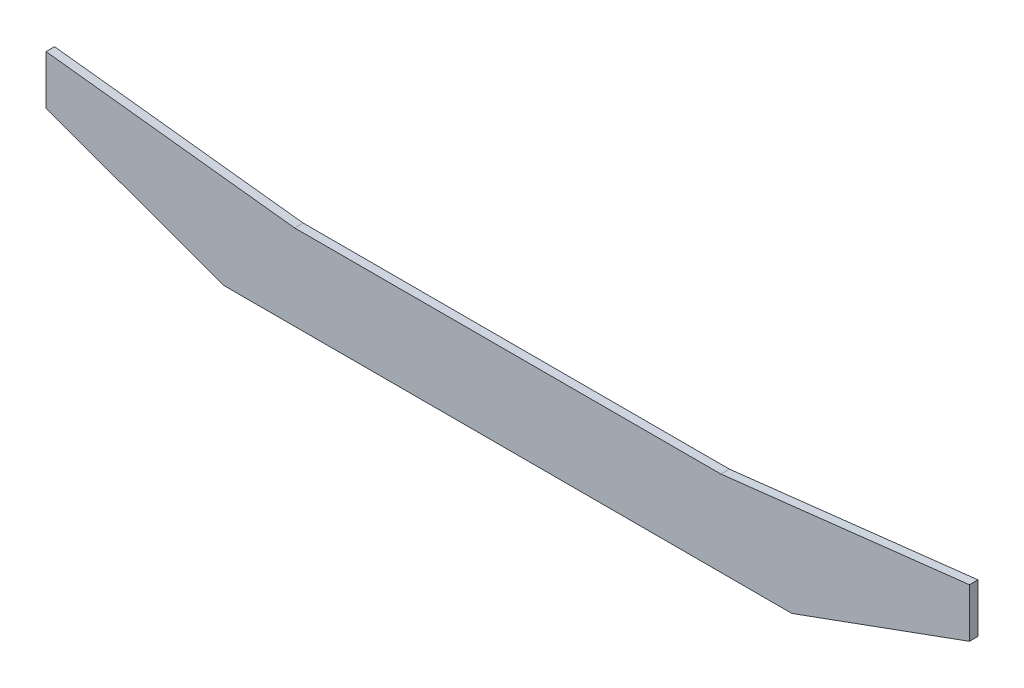
SolidWorks part; units mm, degrees
ref_plane "Спереди" through (0, 0, 0) normal (0, 0, 1) x (1, 0, 0)
ref_plane "Сверху" through (0, 0, 0) normal (0, 1, 0) x (1, 0, 0)
ref_plane "Справа" through (0, 0, 0) normal (1, 0, 0) x (0, 0, -1)
sketch "Эскиз1" plane through (0, 0, 0) normal (0, 0, 1) x (1, 0, 0)
  line L0 (-325, 70.5161) -> (-325, -86.358) construction
  line L1 (325, 74.38) -> (325, -89.8355) construction
  line L2 (-325, 80) -> (-325, 45.4963)
  line L3 (-325, 45.4963) -> (-200, 0)
  line L4 (-200, 0) -> (200, 0)
  line L5 (200, 0) -> (325, 45.4963)
  line L6 (325, 45.4963) -> (325, 80)
  line L8 (-325, 80) -> (-150, 60)
  line L9 (-150, 60) -> (150, 60)
  line L10 (150, 60) -> (325, 80)
  point P15 (-8.3808, 20.5232)
  dimension "D1" = 650
  dimension "D2" = 325
  dimension "D3" = 160
  dimension "D4" = 160
  dimension "D5" = 400
  dimension "D6" = 300
  dimension "D7" = 150
  dimension "D8" = 60
extrude "Бобышка-Вытянуть1" add sketch "Эскиз1" along normal blind 6
